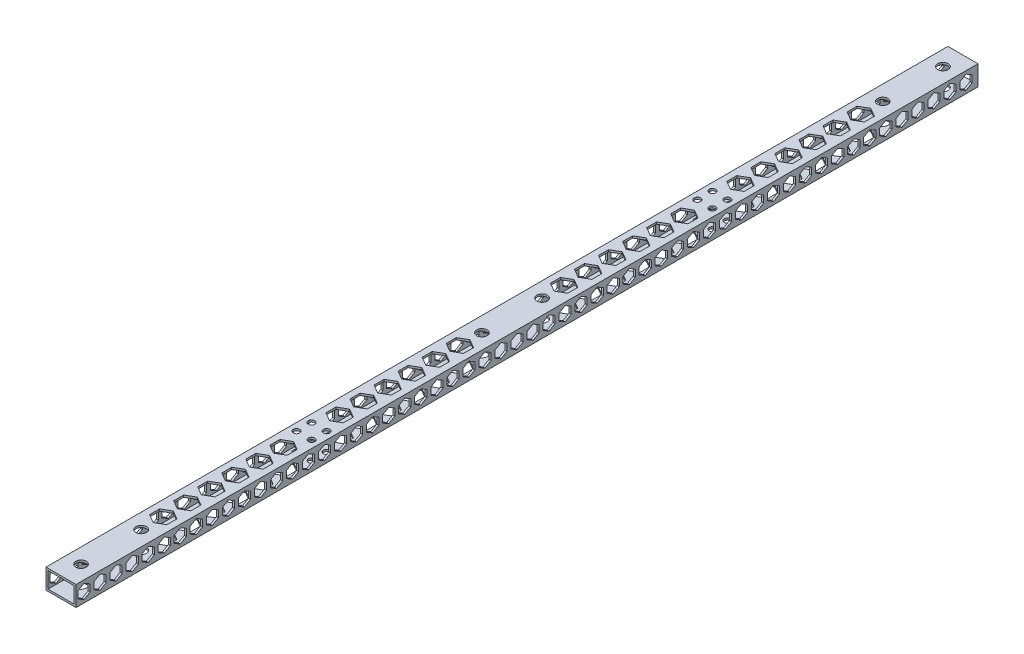
SolidWorks part; units mm, degrees
ref_plane "前视基准面" through (0, 0, 0) normal (0, 0, 1) x (1, 0, 0)
ref_plane "上视基准面" through (0, 0, 0) normal (0, 1, 0) x (1, 0, 0)
ref_plane "右视基准面" through (0, 0, 0) normal (1, 0, 0) x (0, 0, -1)
other "Configuration Table"
sketch "草图1" plane through (0, 0, 0) normal (0, 0, 1) x (1, 0, 0)
  line L1 (0, 0) -> (15, 0)
  line L2 (0, 0) -> (0, -10)
  line L3 (0, -10) -> (15, -10)
  line L4 (15, 0) -> (15, -10)
  dimension "D1" = 15
  dimension "D2" = 10
extrude "拉伸-薄壁1" add sketch "草图1" along normal blind 450 thin
sketch "草图2" plane through (0, -10, 0) normal (0, -1, 0) x (1, 0, 0)
  line L0 (15, 225) -> (0, 225) construction
  line L1 (15, 450) -> (15, 0) construction
  line L2 (0, 450) -> (0, 0) construction
  line L3 (7.5, 450) -> (7.5, 0) construction
  line L4 (0, 450) -> (15, 450) construction
  line L5 (0, 0) -> (15, 0) construction
  line L6 (0, 425) -> (15, 425) construction
  line L7 (0, 325) -> (15, 325) construction
  line L8 (0, 125) -> (15, 125) construction
  line L9 (7.5, 392) -> (3.1699, 389.5)
  line L10 (3.1699, 401.5) -> (3.1699, 396.5)
  line L11 (3.1699, 396.5) -> (7.5, 394)
  line L12 (7.5, 394) -> (11.8301, 396.5)
  line L13 (11.8301, 396.5) -> (11.8301, 401.5)
  line L14 (11.8301, 401.5) -> (7.5, 404)
  line L15 (7.5, 404) -> (3.1699, 401.5)
  line L16 (11.8301, 389.5) -> (7.5, 392)
  line L17 (11.8301, 384.5) -> (11.8301, 389.5)
  line L18 (3.1699, 384.5) -> (7.5, 382)
  line L19 (3.1699, 389.5) -> (3.1699, 384.5)
  line L20 (7.5, 382) -> (11.8301, 384.5)
  line L21 (7.5, 380) -> (3.1699, 377.5)
  line L22 (11.8301, 377.5) -> (7.5, 380)
  line L23 (11.8301, 372.5) -> (11.8301, 377.5)
  line L24 (3.1699, 372.5) -> (7.5, 370)
  line L25 (3.1699, 377.5) -> (3.1699, 372.5)
  line L26 (7.5, 370) -> (11.8301, 372.5)
  line L27 (7.5, 368) -> (3.1699, 365.5)
  line L28 (11.8301, 365.5) -> (7.5, 368)
  line L29 (11.8301, 360.5) -> (11.8301, 365.5)
  line L30 (3.1699, 360.5) -> (7.5, 358)
  line L31 (3.1699, 365.5) -> (3.1699, 360.5)
  line L32 (7.5, 358) -> (11.8301, 360.5)
  line L33 (7.5, 356) -> (3.1699, 353.5)
  line L34 (11.8301, 353.5) -> (7.5, 356)
  line L35 (11.8301, 348.5) -> (11.8301, 353.5)
  line L36 (3.1699, 348.5) -> (7.5, 346)
  line L37 (3.1699, 353.5) -> (3.1699, 348.5)
  line L38 (7.5, 346) -> (11.8301, 348.5)
  line L39 (7.5, 344) -> (3.1699, 341.5)
  line L40 (11.8301, 341.5) -> (7.5, 344)
  line L41 (11.8301, 336.5) -> (11.8301, 341.5)
  line L42 (3.1699, 336.5) -> (7.5, 334)
  line L43 (3.1699, 341.5) -> (3.1699, 336.5)
  line L44 (7.5, 334) -> (11.8301, 336.5)
  line L45 (7.5, 316) -> (11.8301, 313.5)
  line L46 (3.1699, 308.5) -> (3.1699, 313.5)
  line L47 (3.1699, 313.5) -> (7.5, 316)
  line L48 (11.8301, 313.5) -> (11.8301, 308.5)
  line L49 (11.8301, 308.5) -> (7.5, 306)
  line L50 (7.5, 306) -> (3.1699, 308.5)
  line L51 (7.5, 304) -> (11.8301, 301.5)
  line L52 (3.1699, 296.5) -> (3.1699, 301.5)
  line L53 (3.1699, 301.5) -> (7.5, 304)
  line L54 (11.8301, 301.5) -> (11.8301, 296.5)
  line L55 (11.8301, 296.5) -> (7.5, 294)
  line L56 (7.5, 294) -> (3.1699, 296.5)
  line L57 (7.5, 292) -> (11.8301, 289.5)
  line L58 (3.1699, 284.5) -> (3.1699, 289.5)
  line L59 (3.1699, 289.5) -> (7.5, 292)
  line L60 (11.8301, 289.5) -> (11.8301, 284.5)
  line L61 (11.8301, 284.5) -> (7.5, 282)
  line L62 (7.5, 282) -> (3.1699, 284.5)
  line L63 (7.5, 280) -> (11.8301, 277.5)
  line L64 (3.1699, 272.5) -> (3.1699, 277.5)
  line L65 (3.1699, 277.5) -> (7.5, 280)
  line L66 (11.8301, 277.5) -> (11.8301, 272.5)
  line L67 (11.8301, 272.5) -> (7.5, 270)
  line L68 (7.5, 270) -> (3.1699, 272.5)
  line L69 (7.5, 268) -> (11.8301, 265.5)
  line L70 (3.1699, 260.5) -> (3.1699, 265.5)
  line L71 (3.1699, 265.5) -> (7.5, 268)
  line L72 (11.8301, 265.5) -> (11.8301, 260.5)
  line L73 (11.8301, 260.5) -> (7.5, 258)
  line L74 (7.5, 246) -> (3.1699, 248.5)
  line L75 (11.8301, 248.5) -> (7.5, 246)
  line L76 (11.8301, 253.5) -> (11.8301, 248.5)
  line L77 (7.5, 256) -> (11.8301, 253.5)
  line L78 (3.1699, 253.5) -> (7.5, 256)
  line L79 (3.1699, 248.5) -> (3.1699, 253.5)
  line L80 (7.5, 258) -> (3.1699, 260.5)
  line L81 (7.5, 192) -> (3.1699, 189.5)
  line L82 (3.1699, 201.5) -> (3.1699, 196.5)
  line L83 (3.1699, 196.5) -> (7.5, 194)
  line L84 (7.5, 194) -> (11.8301, 196.5)
  line L85 (11.8301, 196.5) -> (11.8301, 201.5)
  line L86 (11.8301, 201.5) -> (7.5, 204)
  line L87 (7.5, 204) -> (3.1699, 201.5)
  line L88 (11.8301, 189.5) -> (7.5, 192)
  line L89 (11.8301, 184.5) -> (11.8301, 189.5)
  line L90 (3.1699, 184.5) -> (7.5, 182)
  line L91 (3.1699, 189.5) -> (3.1699, 184.5)
  line L92 (7.5, 182) -> (11.8301, 184.5)
  line L93 (7.5, 180) -> (3.1699, 177.5)
  line L94 (11.8301, 177.5) -> (7.5, 180)
  line L95 (11.8301, 172.5) -> (11.8301, 177.5)
  line L96 (3.1699, 172.5) -> (7.5, 170)
  line L97 (3.1699, 177.5) -> (3.1699, 172.5)
  line L98 (7.5, 170) -> (11.8301, 172.5)
  line L99 (7.5, 168) -> (3.1699, 165.5)
  line L100 (11.8301, 165.5) -> (7.5, 168)
  line L101 (11.8301, 160.5) -> (11.8301, 165.5)
  line L102 (3.1699, 160.5) -> (7.5, 158)
  line L103 (3.1699, 165.5) -> (3.1699, 160.5)
  line L104 (7.5, 158) -> (11.8301, 160.5)
  line L105 (7.5, 156) -> (3.1699, 153.5)
  line L106 (11.8301, 153.5) -> (7.5, 156)
  line L107 (11.8301, 148.5) -> (11.8301, 153.5)
  line L108 (3.1699, 148.5) -> (7.5, 146)
  line L109 (3.1699, 153.5) -> (3.1699, 148.5)
  line L110 (7.5, 146) -> (11.8301, 148.5)
  line L111 (7.5, 144) -> (3.1699, 141.5)
  line L112 (11.8301, 141.5) -> (7.5, 144)
  line L113 (11.8301, 136.5) -> (11.8301, 141.5)
  line L114 (3.1699, 136.5) -> (7.5, 134)
  line L115 (3.1699, 141.5) -> (3.1699, 136.5)
  line L116 (7.5, 134) -> (11.8301, 136.5)
  line L117 (7.5, 116) -> (11.8301, 113.5)
  line L118 (3.1699, 108.5) -> (3.1699, 113.5)
  line L119 (3.1699, 113.5) -> (7.5, 116)
  line L120 (11.8301, 113.5) -> (11.8301, 108.5)
  line L121 (11.8301, 108.5) -> (7.5, 106)
  line L122 (7.5, 106) -> (3.1699, 108.5)
  line L123 (7.5, 104) -> (11.8301, 101.5)
  line L124 (3.1699, 96.5) -> (3.1699, 101.5)
  line L125 (3.1699, 101.5) -> (7.5, 104)
  line L126 (11.8301, 101.5) -> (11.8301, 96.5)
  line L127 (11.8301, 96.5) -> (7.5, 94)
  line L128 (7.5, 94) -> (3.1699, 96.5)
  line L129 (7.5, 92) -> (11.8301, 89.5)
  line L130 (3.1699, 84.5) -> (3.1699, 89.5)
  line L131 (3.1699, 89.5) -> (7.5, 92)
  line L132 (11.8301, 89.5) -> (11.8301, 84.5)
  line L133 (11.8301, 84.5) -> (7.5, 82)
  line L134 (7.5, 82) -> (3.1699, 84.5)
  line L135 (7.5, 80) -> (11.8301, 77.5)
  line L136 (3.1699, 72.5) -> (3.1699, 77.5)
  line L137 (3.1699, 77.5) -> (7.5, 80)
  line L138 (11.8301, 77.5) -> (11.8301, 72.5)
  line L139 (11.8301, 72.5) -> (7.5, 70)
  line L140 (7.5, 70) -> (3.1699, 72.5)
  line L141 (7.5, 68) -> (11.8301, 65.5)
  line L142 (3.1699, 60.5) -> (3.1699, 65.5)
  line L143 (3.1699, 65.5) -> (7.5, 68)
  line L144 (11.8301, 65.5) -> (11.8301, 60.5)
  line L145 (11.8301, 60.5) -> (7.5, 58)
  line L146 (7.5, 46) -> (3.1699, 48.5)
  line L147 (11.8301, 48.5) -> (7.5, 46)
  line L148 (11.8301, 53.5) -> (11.8301, 48.5)
  line L149 (7.5, 56) -> (11.8301, 53.5)
  line L150 (3.1699, 53.5) -> (7.5, 56)
  line L151 (3.1699, 48.5) -> (3.1699, 53.5)
  line L152 (7.5, 58) -> (3.1699, 60.5)
  circle A0 centre (7.5, 240) radius 2.6
  circle A1 centre (7.5, 210) radius 2.6
  circle A2 centre (7.5, 440) radius 2.6
  circle A3 centre (7.5, 410) radius 2.6
  circle A4 centre (7.5, 40) radius 2.6
  circle A5 centre (7.5, 10) radius 2.6
  circle A6 centre (3.75, 328.75) radius 1.6
  circle A7 centre (11.25, 328.75) radius 1.6
  circle A8 centre (11.25, 321.25) radius 1.6
  circle A9 centre (3.75, 321.25) radius 1.6
  circle A10 centre (3.75, 128.75) radius 1.6
  circle A11 centre (11.25, 128.75) radius 1.6
  circle A12 centre (11.25, 121.25) radius 1.6
  circle A13 centre (3.75, 121.25) radius 1.6
  circle A14 centre (7.5, 399) radius 4.3301 construction
  circle A15 centre (7.5, 251) radius 4.3301 construction
  circle A16 centre (7.5, 199) radius 4.3301 construction
  circle A17 centre (7.5, 51) radius 4.3301 construction
  point P84 (0, 0)
  point P85 (0, 0)
  dimension "D1" = 15
  dimension "D2" = 5.2
  dimension "D4" = 5.2
  dimension "D7" = 3.2
  dimension "D3" = 200
  dimension "D5" = 15
  dimension "D6" = 100
  dimension "D8" = 3.75
  dimension "D9" = 3.75
  dimension "D10" = 11
  dimension "D11" = 5
  dimension "D13" = 12
  dimension "D12" = 6
extrude "切除-拉伸1" cut sketch "草图2" against normal through all
sketch "草图3" plane through (0, 0, 0) normal (-1, 0, 0) x (0, 0, 1)
  line L0 (6, -5) -> (0, -5) construction
  line L1 (9.0311, -6.75) -> (9.0311, -3.25)
  line L2 (9.0311, -3.25) -> (6, -1.5)
  line L3 (6, -1.5) -> (2.9689, -3.25)
  line L4 (2.9689, -3.25) -> (2.9689, -6.75)
  line L5 (2.9689, -6.75) -> (6, -8.5)
  line L6 (6, -8.5) -> (9.0311, -6.75)
  line L7 (0, 0) -> (0, -10) construction
  line L8 (14, -1.5) -> (10.9689, -3.25)
  line L9 (17.0311, -3.25) -> (14, -1.5)
  line L10 (17.0311, -6.75) -> (17.0311, -3.25)
  line L11 (14, -8.5) -> (17.0311, -6.75)
  line L12 (10.9689, -6.75) -> (14, -8.5)
  line L13 (10.9689, -3.25) -> (10.9689, -6.75)
  line L14 (22, -1.5) -> (18.9689, -3.25)
  line L15 (25.0311, -3.25) -> (22, -1.5)
  line L16 (25.0311, -6.75) -> (25.0311, -3.25)
  line L17 (22, -8.5) -> (25.0311, -6.75)
  line L18 (18.9689, -6.75) -> (22, -8.5)
  line L19 (18.9689, -3.25) -> (18.9689, -6.75)
  line L20 (30, -1.5) -> (26.9689, -3.25)
  line L21 (33.0311, -3.25) -> (30, -1.5)
  line L22 (33.0311, -6.75) -> (33.0311, -3.25)
  line L23 (30, -8.5) -> (33.0311, -6.75)
  line L24 (26.9689, -6.75) -> (30, -8.5)
  line L25 (26.9689, -3.25) -> (26.9689, -6.75)
  line L26 (38, -1.5) -> (34.9689, -3.25)
  line L27 (41.0311, -3.25) -> (38, -1.5)
  line L28 (41.0311, -6.75) -> (41.0311, -3.25)
  line L29 (38, -8.5) -> (41.0311, -6.75)
  line L30 (34.9689, -6.75) -> (38, -8.5)
  line L31 (34.9689, -3.25) -> (34.9689, -6.75)
  line L32 (46, -1.5) -> (42.9689, -3.25)
  line L33 (49.0311, -3.25) -> (46, -1.5)
  line L34 (49.0311, -6.75) -> (49.0311, -3.25)
  line L35 (46, -8.5) -> (49.0311, -6.75)
  line L36 (42.9689, -6.75) -> (46, -8.5)
  line L37 (42.9689, -3.25) -> (42.9689, -6.75)
  line L38 (54, -1.5) -> (50.9689, -3.25)
  line L39 (57.0311, -3.25) -> (54, -1.5)
  line L40 (57.0311, -6.75) -> (57.0311, -3.25)
  line L41 (54, -8.5) -> (57.0311, -6.75)
  line L42 (50.9689, -6.75) -> (54, -8.5)
  line L43 (50.9689, -3.25) -> (50.9689, -6.75)
  line L44 (62, -1.5) -> (58.9689, -3.25)
  line L45 (65.0311, -3.25) -> (62, -1.5)
  line L46 (65.0311, -6.75) -> (65.0311, -3.25)
  line L47 (62, -8.5) -> (65.0311, -6.75)
  line L48 (58.9689, -6.75) -> (62, -8.5)
  line L49 (58.9689, -3.25) -> (58.9689, -6.75)
  line L50 (70, -1.5) -> (66.9689, -3.25)
  line L51 (73.0311, -3.25) -> (70, -1.5)
  line L52 (73.0311, -6.75) -> (73.0311, -3.25)
  line L53 (70, -8.5) -> (73.0311, -6.75)
  line L54 (66.9689, -6.75) -> (70, -8.5)
  line L55 (66.9689, -3.25) -> (66.9689, -6.75)
  line L56 (78, -1.5) -> (74.9689, -3.25)
  line L57 (81.0311, -3.25) -> (78, -1.5)
  line L58 (81.0311, -6.75) -> (81.0311, -3.25)
  line L59 (78, -8.5) -> (81.0311, -6.75)
  line L60 (74.9689, -6.75) -> (78, -8.5)
  line L61 (74.9689, -3.25) -> (74.9689, -6.75)
  line L62 (86, -1.5) -> (82.9689, -3.25)
  line L63 (89.0311, -3.25) -> (86, -1.5)
  line L64 (89.0311, -6.75) -> (89.0311, -3.25)
  line L65 (86, -8.5) -> (89.0311, -6.75)
  line L66 (82.9689, -6.75) -> (86, -8.5)
  line L67 (82.9689, -3.25) -> (82.9689, -6.75)
  line L68 (94, -1.5) -> (90.9689, -3.25)
  line L69 (97.0311, -3.25) -> (94, -1.5)
  line L70 (97.0311, -6.75) -> (97.0311, -3.25)
  line L71 (94, -8.5) -> (97.0311, -6.75)
  line L72 (90.9689, -6.75) -> (94, -8.5)
  line L73 (90.9689, -3.25) -> (90.9689, -6.75)
  line L74 (102, -1.5) -> (98.9689, -3.25)
  line L75 (105.0311, -3.25) -> (102, -1.5)
  line L76 (105.0311, -6.75) -> (105.0311, -3.25)
  line L77 (102, -8.5) -> (105.0311, -6.75)
  line L78 (98.9689, -6.75) -> (102, -8.5)
  line L79 (98.9689, -3.25) -> (98.9689, -6.75)
  line L80 (110, -1.5) -> (106.9689, -3.25)
  line L81 (113.0311, -3.25) -> (110, -1.5)
  line L82 (113.0311, -6.75) -> (113.0311, -3.25)
  line L83 (110, -8.5) -> (113.0311, -6.75)
  line L84 (106.9689, -6.75) -> (110, -8.5)
  line L85 (106.9689, -3.25) -> (106.9689, -6.75)
  line L86 (118, -1.5) -> (114.9689, -3.25)
  line L87 (121.0311, -3.25) -> (118, -1.5)
  line L88 (121.0311, -6.75) -> (121.0311, -3.25)
  line L89 (118, -8.5) -> (121.0311, -6.75)
  line L90 (114.9689, -6.75) -> (118, -8.5)
  line L91 (114.9689, -3.25) -> (114.9689, -6.75)
  line L92 (126, -1.5) -> (122.9689, -3.25)
  line L93 (129.0311, -3.25) -> (126, -1.5)
  line L94 (129.0311, -6.75) -> (129.0311, -3.25)
  line L95 (126, -8.5) -> (129.0311, -6.75)
  line L96 (122.9689, -6.75) -> (126, -8.5)
  line L97 (122.9689, -3.25) -> (122.9689, -6.75)
  line L98 (134, -1.5) -> (130.9689, -3.25)
  line L99 (137.0311, -3.25) -> (134, -1.5)
  line L100 (137.0311, -6.75) -> (137.0311, -3.25)
  line L101 (134, -8.5) -> (137.0311, -6.75)
  line L102 (130.9689, -6.75) -> (134, -8.5)
  line L103 (130.9689, -3.25) -> (130.9689, -6.75)
  line L104 (142, -1.5) -> (138.9689, -3.25)
  line L105 (145.0311, -3.25) -> (142, -1.5)
  line L106 (145.0311, -6.75) -> (145.0311, -3.25)
  line L107 (142, -8.5) -> (145.0311, -6.75)
  line L108 (138.9689, -6.75) -> (142, -8.5)
  line L109 (138.9689, -3.25) -> (138.9689, -6.75)
  line L110 (150, -1.5) -> (146.9689, -3.25)
  line L111 (153.0311, -3.25) -> (150, -1.5)
  line L112 (153.0311, -6.75) -> (153.0311, -3.25)
  line L113 (150, -8.5) -> (153.0311, -6.75)
  line L114 (146.9689, -6.75) -> (150, -8.5)
  line L115 (146.9689, -3.25) -> (146.9689, -6.75)
  line L116 (158, -1.5) -> (154.9689, -3.25)
  line L117 (161.0311, -3.25) -> (158, -1.5)
  line L118 (161.0311, -6.75) -> (161.0311, -3.25)
  line L119 (158, -8.5) -> (161.0311, -6.75)
  line L120 (154.9689, -6.75) -> (158, -8.5)
  line L121 (154.9689, -3.25) -> (154.9689, -6.75)
  line L122 (166, -1.5) -> (162.9689, -3.25)
  line L123 (169.0311, -3.25) -> (166, -1.5)
  line L124 (169.0311, -6.75) -> (169.0311, -3.25)
  line L125 (166, -8.5) -> (169.0311, -6.75)
  line L126 (162.9689, -6.75) -> (166, -8.5)
  line L127 (162.9689, -3.25) -> (162.9689, -6.75)
  line L128 (174, -1.5) -> (170.9689, -3.25)
  line L129 (177.0311, -3.25) -> (174, -1.5)
  line L130 (177.0311, -6.75) -> (177.0311, -3.25)
  line L131 (174, -8.5) -> (177.0311, -6.75)
  line L132 (170.9689, -6.75) -> (174, -8.5)
  line L133 (170.9689, -3.25) -> (170.9689, -6.75)
  line L134 (182, -1.5) -> (178.9689, -3.25)
  line L135 (185.0311, -3.25) -> (182, -1.5)
  line L136 (185.0311, -6.75) -> (185.0311, -3.25)
  line L137 (182, -8.5) -> (185.0311, -6.75)
  line L138 (178.9689, -6.75) -> (182, -8.5)
  line L139 (178.9689, -3.25) -> (178.9689, -6.75)
  line L140 (190, -1.5) -> (186.9689, -3.25)
  line L141 (193.0311, -3.25) -> (190, -1.5)
  line L142 (193.0311, -6.75) -> (193.0311, -3.25)
  line L143 (190, -8.5) -> (193.0311, -6.75)
  line L144 (186.9689, -6.75) -> (190, -8.5)
  line L145 (186.9689, -3.25) -> (186.9689, -6.75)
  line L146 (198, -1.5) -> (194.9689, -3.25)
  line L147 (201.0311, -3.25) -> (198, -1.5)
  line L148 (201.0311, -6.75) -> (201.0311, -3.25)
  line L149 (198, -8.5) -> (201.0311, -6.75)
  line L150 (194.9689, -6.75) -> (198, -8.5)
  line L151 (194.9689, -3.25) -> (194.9689, -6.75)
  line L152 (206, -1.5) -> (202.9689, -3.25)
  line L153 (209.0311, -3.25) -> (206, -1.5)
  line L154 (209.0311, -6.75) -> (209.0311, -3.25)
  line L155 (206, -8.5) -> (209.0311, -6.75)
  line L156 (202.9689, -6.75) -> (206, -8.5)
  line L157 (202.9689, -3.25) -> (202.9689, -6.75)
  line L158 (214, -1.5) -> (210.9689, -3.25)
  line L159 (217.0311, -3.25) -> (214, -1.5)
  line L160 (217.0311, -6.75) -> (217.0311, -3.25)
  line L161 (214, -8.5) -> (217.0311, -6.75)
  line L162 (210.9689, -6.75) -> (214, -8.5)
  line L163 (210.9689, -3.25) -> (210.9689, -6.75)
  line L164 (222, -1.5) -> (218.9689, -3.25)
  line L165 (225.0311, -3.25) -> (222, -1.5)
  line L166 (225.0311, -6.75) -> (225.0311, -3.25)
  line L167 (222, -8.5) -> (225.0311, -6.75)
  line L168 (218.9689, -6.75) -> (222, -8.5)
  line L169 (218.9689, -3.25) -> (218.9689, -6.75)
  line L170 (230, -1.5) -> (226.9689, -3.25)
  line L171 (233.0311, -3.25) -> (230, -1.5)
  line L172 (233.0311, -6.75) -> (233.0311, -3.25)
  line L173 (230, -8.5) -> (233.0311, -6.75)
  line L174 (226.9689, -6.75) -> (230, -8.5)
  line L175 (226.9689, -3.25) -> (226.9689, -6.75)
  line L176 (238, -1.5) -> (234.9689, -3.25)
  line L177 (241.0311, -3.25) -> (238, -1.5)
  line L178 (241.0311, -6.75) -> (241.0311, -3.25)
  line L179 (238, -8.5) -> (241.0311, -6.75)
  line L180 (234.9689, -6.75) -> (238, -8.5)
  line L181 (234.9689, -3.25) -> (234.9689, -6.75)
  line L182 (246, -1.5) -> (242.9689, -3.25)
  line L183 (249.0311, -3.25) -> (246, -1.5)
  line L184 (249.0311, -6.75) -> (249.0311, -3.25)
  line L185 (246, -8.5) -> (249.0311, -6.75)
  line L186 (242.9689, -6.75) -> (246, -8.5)
  line L187 (242.9689, -3.25) -> (242.9689, -6.75)
  line L188 (254, -1.5) -> (250.9689, -3.25)
  line L189 (257.0311, -3.25) -> (254, -1.5)
  line L190 (257.0311, -6.75) -> (257.0311, -3.25)
  line L191 (254, -8.5) -> (257.0311, -6.75)
  line L192 (250.9689, -6.75) -> (254, -8.5)
  line L193 (250.9689, -3.25) -> (250.9689, -6.75)
  line L194 (262, -1.5) -> (258.9689, -3.25)
  line L195 (265.0311, -3.25) -> (262, -1.5)
  line L196 (265.0311, -6.75) -> (265.0311, -3.25)
  line L197 (262, -8.5) -> (265.0311, -6.75)
  line L198 (258.9689, -6.75) -> (262, -8.5)
  line L199 (258.9689, -3.25) -> (258.9689, -6.75)
  line L200 (270, -1.5) -> (266.9689, -3.25)
  line L201 (273.0311, -3.25) -> (270, -1.5)
  line L202 (273.0311, -6.75) -> (273.0311, -3.25)
  line L203 (270, -8.5) -> (273.0311, -6.75)
  line L204 (266.9689, -6.75) -> (270, -8.5)
  line L205 (266.9689, -3.25) -> (266.9689, -6.75)
  line L206 (278, -1.5) -> (274.9689, -3.25)
  line L207 (281.0311, -3.25) -> (278, -1.5)
  line L208 (281.0311, -6.75) -> (281.0311, -3.25)
  line L209 (278, -8.5) -> (281.0311, -6.75)
  line L210 (274.9689, -6.75) -> (278, -8.5)
  line L211 (274.9689, -3.25) -> (274.9689, -6.75)
  line L212 (286, -1.5) -> (282.9689, -3.25)
  line L213 (289.0311, -3.25) -> (286, -1.5)
  line L214 (289.0311, -6.75) -> (289.0311, -3.25)
  line L215 (286, -8.5) -> (289.0311, -6.75)
  line L216 (282.9689, -6.75) -> (286, -8.5)
  line L217 (282.9689, -3.25) -> (282.9689, -6.75)
  line L218 (294, -1.5) -> (290.9689, -3.25)
  line L219 (297.0311, -3.25) -> (294, -1.5)
  line L220 (297.0311, -6.75) -> (297.0311, -3.25)
  line L221 (294, -8.5) -> (297.0311, -6.75)
  line L222 (290.9689, -6.75) -> (294, -8.5)
  line L223 (290.9689, -3.25) -> (290.9689, -6.75)
  line L224 (302, -1.5) -> (298.9689, -3.25)
  line L225 (305.0311, -3.25) -> (302, -1.5)
  line L226 (305.0311, -6.75) -> (305.0311, -3.25)
  line L227 (302, -8.5) -> (305.0311, -6.75)
  line L228 (298.9689, -6.75) -> (302, -8.5)
  line L229 (298.9689, -3.25) -> (298.9689, -6.75)
  line L230 (310, -1.5) -> (306.9689, -3.25)
  line L231 (313.0311, -3.25) -> (310, -1.5)
  line L232 (313.0311, -6.75) -> (313.0311, -3.25)
  line L233 (310, -8.5) -> (313.0311, -6.75)
  line L234 (306.9689, -6.75) -> (310, -8.5)
  line L235 (306.9689, -3.25) -> (306.9689, -6.75)
  line L236 (318, -1.5) -> (314.9689, -3.25)
  line L237 (321.0311, -3.25) -> (318, -1.5)
  line L238 (321.0311, -6.75) -> (321.0311, -3.25)
  line L239 (318, -8.5) -> (321.0311, -6.75)
  line L240 (314.9689, -6.75) -> (318, -8.5)
  line L241 (314.9689, -3.25) -> (314.9689, -6.75)
  line L242 (326, -1.5) -> (322.9689, -3.25)
  line L243 (329.0311, -3.25) -> (326, -1.5)
  line L244 (329.0311, -6.75) -> (329.0311, -3.25)
  line L245 (326, -8.5) -> (329.0311, -6.75)
  line L246 (322.9689, -6.75) -> (326, -8.5)
  line L247 (322.9689, -3.25) -> (322.9689, -6.75)
  line L248 (334, -1.5) -> (330.9689, -3.25)
  line L249 (337.0311, -3.25) -> (334, -1.5)
  line L250 (337.0311, -6.75) -> (337.0311, -3.25)
  line L251 (334, -8.5) -> (337.0311, -6.75)
  line L252 (330.9689, -6.75) -> (334, -8.5)
  line L253 (330.9689, -3.25) -> (330.9689, -6.75)
  line L254 (342, -1.5) -> (338.9689, -3.25)
  line L255 (345.0311, -3.25) -> (342, -1.5)
  line L256 (345.0311, -6.75) -> (345.0311, -3.25)
  line L257 (342, -8.5) -> (345.0311, -6.75)
  line L258 (338.9689, -6.75) -> (342, -8.5)
  line L259 (338.9689, -3.25) -> (338.9689, -6.75)
  line L260 (350, -1.5) -> (346.9689, -3.25)
  line L261 (353.0311, -3.25) -> (350, -1.5)
  line L262 (353.0311, -6.75) -> (353.0311, -3.25)
  line L263 (350, -8.5) -> (353.0311, -6.75)
  line L264 (346.9689, -6.75) -> (350, -8.5)
  line L265 (346.9689, -3.25) -> (346.9689, -6.75)
  line L266 (358, -1.5) -> (354.9689, -3.25)
  line L267 (361.0311, -3.25) -> (358, -1.5)
  line L268 (361.0311, -6.75) -> (361.0311, -3.25)
  line L269 (358, -8.5) -> (361.0311, -6.75)
  line L270 (354.9689, -6.75) -> (358, -8.5)
  line L271 (354.9689, -3.25) -> (354.9689, -6.75)
  line L272 (366, -1.5) -> (362.9689, -3.25)
  line L273 (369.0311, -3.25) -> (366, -1.5)
  line L274 (369.0311, -6.75) -> (369.0311, -3.25)
  line L275 (366, -8.5) -> (369.0311, -6.75)
  line L276 (362.9689, -6.75) -> (366, -8.5)
  line L277 (362.9689, -3.25) -> (362.9689, -6.75)
  line L278 (374, -1.5) -> (370.9689, -3.25)
  line L279 (377.0311, -3.25) -> (374, -1.5)
  line L280 (377.0311, -6.75) -> (377.0311, -3.25)
  line L281 (374, -8.5) -> (377.0311, -6.75)
  line L282 (370.9689, -6.75) -> (374, -8.5)
  line L283 (370.9689, -3.25) -> (370.9689, -6.75)
  line L284 (382, -1.5) -> (378.9689, -3.25)
  line L285 (385.0311, -3.25) -> (382, -1.5)
  line L286 (385.0311, -6.75) -> (385.0311, -3.25)
  line L287 (382, -8.5) -> (385.0311, -6.75)
  line L288 (378.9689, -6.75) -> (382, -8.5)
  line L289 (378.9689, -3.25) -> (378.9689, -6.75)
  line L290 (390, -1.5) -> (386.9689, -3.25)
  line L291 (393.0311, -3.25) -> (390, -1.5)
  line L292 (393.0311, -6.75) -> (393.0311, -3.25)
  line L293 (390, -8.5) -> (393.0311, -6.75)
  line L294 (386.9689, -6.75) -> (390, -8.5)
  line L295 (386.9689, -3.25) -> (386.9689, -6.75)
  line L296 (398, -1.5) -> (394.9689, -3.25)
  line L297 (401.0311, -3.25) -> (398, -1.5)
  line L298 (401.0311, -6.75) -> (401.0311, -3.25)
  line L299 (398, -8.5) -> (401.0311, -6.75)
  line L300 (394.9689, -6.75) -> (398, -8.5)
  line L301 (394.9689, -3.25) -> (394.9689, -6.75)
  line L302 (406, -1.5) -> (402.9689, -3.25)
  line L303 (409.0311, -3.25) -> (406, -1.5)
  line L304 (409.0311, -6.75) -> (409.0311, -3.25)
  line L305 (406, -8.5) -> (409.0311, -6.75)
  line L306 (402.9689, -6.75) -> (406, -8.5)
  line L307 (402.9689, -3.25) -> (402.9689, -6.75)
  line L308 (414, -1.5) -> (410.9689, -3.25)
  line L309 (417.0311, -3.25) -> (414, -1.5)
  line L310 (417.0311, -6.75) -> (417.0311, -3.25)
  line L311 (414, -8.5) -> (417.0311, -6.75)
  line L312 (410.9689, -6.75) -> (414, -8.5)
  line L313 (410.9689, -3.25) -> (410.9689, -6.75)
  line L314 (422, -1.5) -> (418.9689, -3.25)
  line L315 (425.0311, -3.25) -> (422, -1.5)
  line L316 (425.0311, -6.75) -> (425.0311, -3.25)
  line L317 (422, -8.5) -> (425.0311, -6.75)
  line L318 (418.9689, -6.75) -> (422, -8.5)
  line L319 (418.9689, -3.25) -> (418.9689, -6.75)
  line L320 (430, -1.5) -> (426.9689, -3.25)
  line L321 (433.0311, -3.25) -> (430, -1.5)
  line L322 (433.0311, -6.75) -> (433.0311, -3.25)
  line L323 (430, -8.5) -> (433.0311, -6.75)
  line L324 (426.9689, -6.75) -> (430, -8.5)
  line L325 (426.9689, -3.25) -> (426.9689, -6.75)
  line L326 (438, -1.5) -> (434.9689, -3.25)
  line L327 (441.0311, -3.25) -> (438, -1.5)
  line L328 (441.0311, -6.75) -> (441.0311, -3.25)
  line L329 (438, -8.5) -> (441.0311, -6.75)
  line L330 (434.9689, -6.75) -> (438, -8.5)
  line L331 (434.9689, -3.25) -> (434.9689, -6.75)
  line L332 (446, -1.5) -> (442.9689, -3.25)
  line L333 (449.0311, -3.25) -> (446, -1.5)
  line L334 (449.0311, -6.75) -> (449.0311, -3.25)
  line L335 (446, -8.5) -> (449.0311, -6.75)
  line L336 (442.9689, -6.75) -> (446, -8.5)
  line L337 (442.9689, -3.25) -> (442.9689, -6.75)
  circle A0 centre (6, -5) radius 3.0311 construction
  dimension "D1" = 3.5
  dimension "D2" = 6
  dimension "D4" = 8
  dimension "D3" = 56
extrude "切除-拉伸2" cut sketch "草图3" against normal through all
